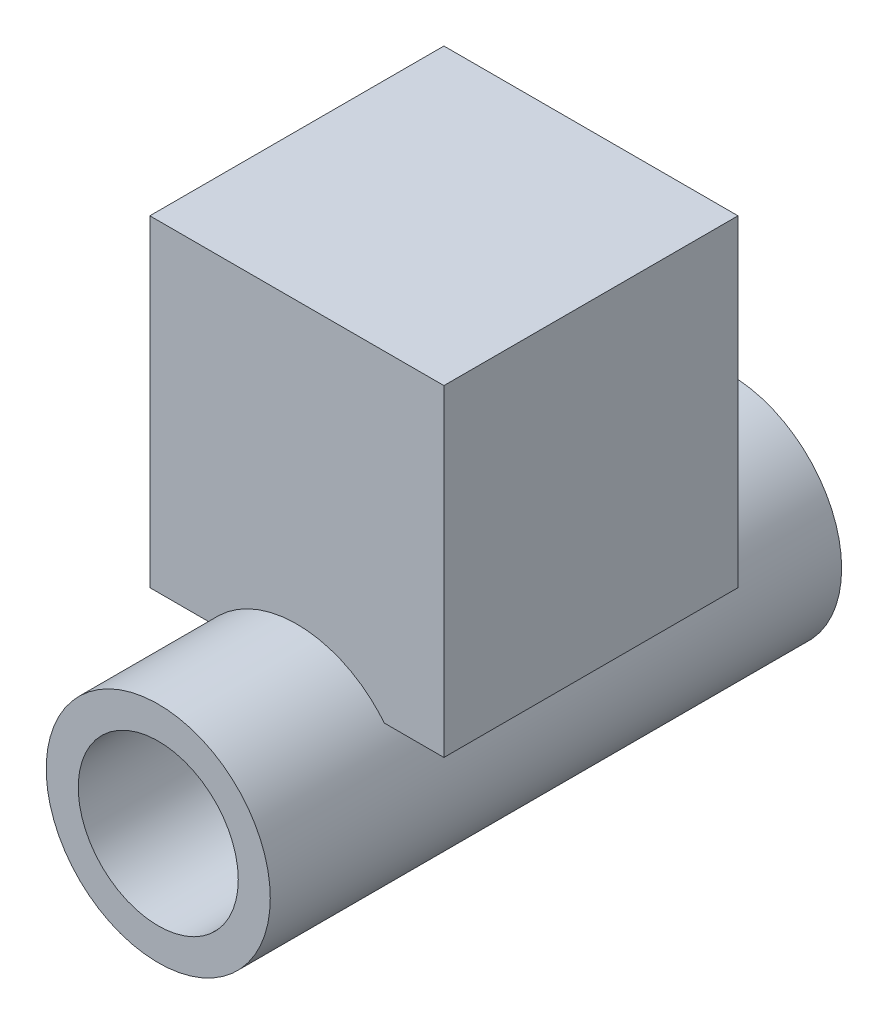
SolidWorks part; units mm, degrees
material "Brass"
ref_plane "Front Plane" through (0, 0, 0) normal (0, 0, 1) x (1, 0, 0)
ref_plane "Top Plane" through (0, 0, 0) normal (0, 1, 0) x (1, 0, 0)
ref_plane "Right Plane" through (0, 0, 0) normal (1, 0, 0) x (0, 0, -1)
sketch "Sketch1" plane through (0, 0, 0) normal (0, 0, 1) x (1, 0, 0)
  circle A0 centre (0, 0) radius 13.335
  circle A1 centre (0, 0) radius 9.525
  dimension "D1" = 26.67
  dimension "D2" = 19.05
extrude "Boss-Extrude1" add sketch "Sketch1" against normal blind 68
ref_plane "Plane1" through (0, 13.335, 0) normal (0, 1, 0) x (0, 0, -1)
sketch "Sketch3" plane through (0, 13.335, 0) normal (0, 1, 0) x (0, 0, -1)
  line L0 (0, 0) -> (68, 0) construction
  line L1 (16.5, 17.5) -> (51.5, 17.5)
  line L2 (16.5, 17.5) -> (16.5, -17.5)
  line L3 (16.5, -17.5) -> (51.5, -17.5)
  line L4 (51.5, 17.5) -> (51.5, -17.5)
  line L5 (16.5, 17.5) -> (51.5, -17.5) construction
  line L6 (16.5, -17.5) -> (51.5, 17.5) construction
  line L7 (68, -13.335) -> (68, 13.335) construction
  point P0 (34, 0)
  point P10 (0, 0)
  dimension "D1" = 35
  dimension "D2" = 35
extrude "Boss-Extrude2" add sketch "Sketch3" along normal blind 33.33 and the other way blind 5 separate body
